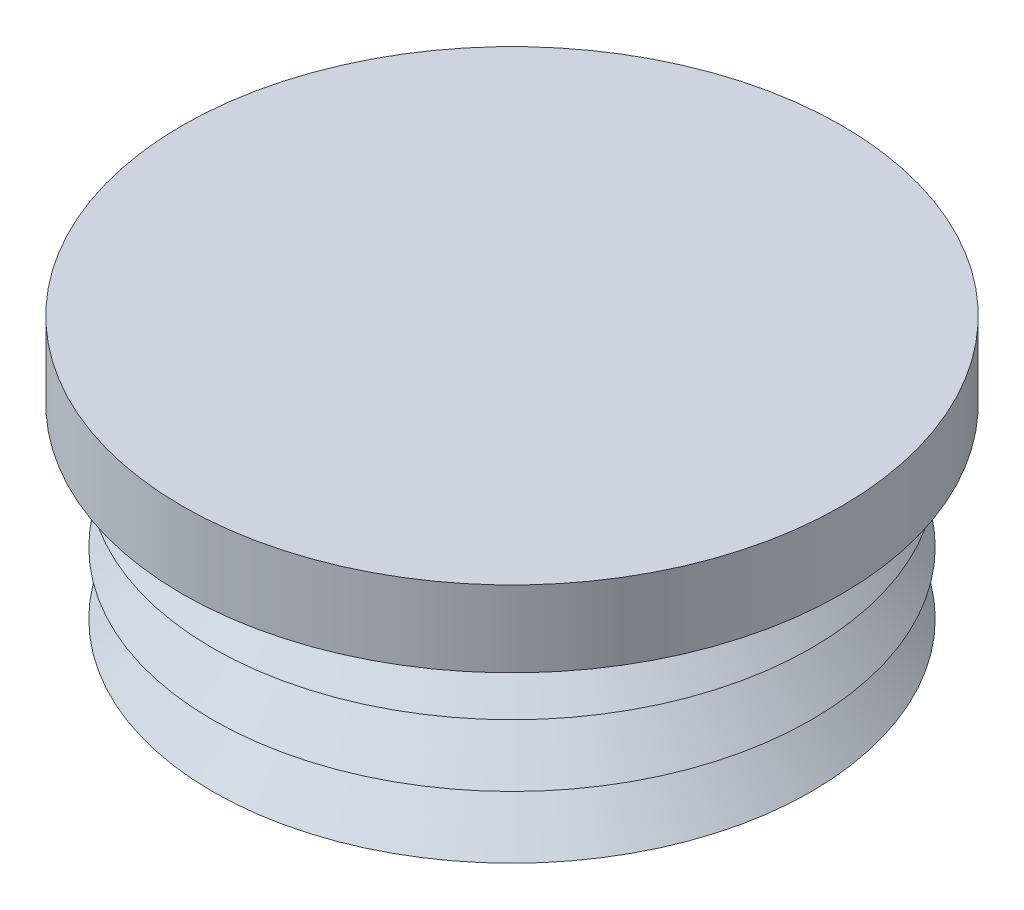
SolidWorks part; units mm, degrees
ref_plane "Front Plane" through (0, 0, 0) normal (0, 0, 1) x (1, 0, 0)
ref_plane "Top Plane" through (0, 0, 0) normal (0, 1, 0) x (1, 0, 0)
ref_plane "Right Plane" through (0, 0, 0) normal (1, 0, 0) x (0, 0, -1)
sketch "Sketch1" plane through (0, 0, 0) normal (0, 0, 1) x (1, 0, 0)
  line L0 (0, 0) -> (0, 12.7) construction
  line L1 (0, 12.7) -> (0, 17.4625) construction
  line L2 (15.875, 0) -> (15.875, 1.0319)
  line L3 (15.875, 1.0319) -> (18.7325, 1.0319)
  line L4 (18.7325, 1.0319) -> (15.875, 3.8894)
  line L5 (15.875, 3.8894) -> (15.875, 4.9213)
  line L6 (15.875, 4.9213) -> (18.7325, 4.9213)
  line L7 (18.7325, 4.9213) -> (15.875, 7.7787)
  line L8 (15.875, 7.7787) -> (15.875, 8.8106)
  line L9 (15.875, 8.8106) -> (18.7325, 8.8106)
  line L10 (18.7325, 8.8106) -> (15.875, 11.6681)
  line L11 (15.875, 11.6681) -> (15.875, 12.7)
  line L12 (15.875, 12.7) -> (20.6375, 12.7)
  line L13 (20.6375, 12.7) -> (20.6375, 17.4625)
  line L14 (20.6375, 17.4625) -> (0, 17.4625)
  line L15 (0, 12.7) -> (14.9225, 12.7)
  line L16 (14.9225, 12.7) -> (14.9225, 0)
  line L17 (14.9225, 0) -> (15.875, 0)
  line L18 (0, 12.7) -> (0, 17.4625)
  dimension "D1" = 12.7
  dimension "D2" = 4.7625
  dimension "D3" = 37.465
  dimension "D4" = 31.75
  dimension "D5" = 45
  dimension "D6" = 29.845
  dimension "D7" = 41.275
revolve "Revolve1" add sketch "Sketch1" angle 360 about L0
fillet "Fillet1" [suppressed] radius 3.175
